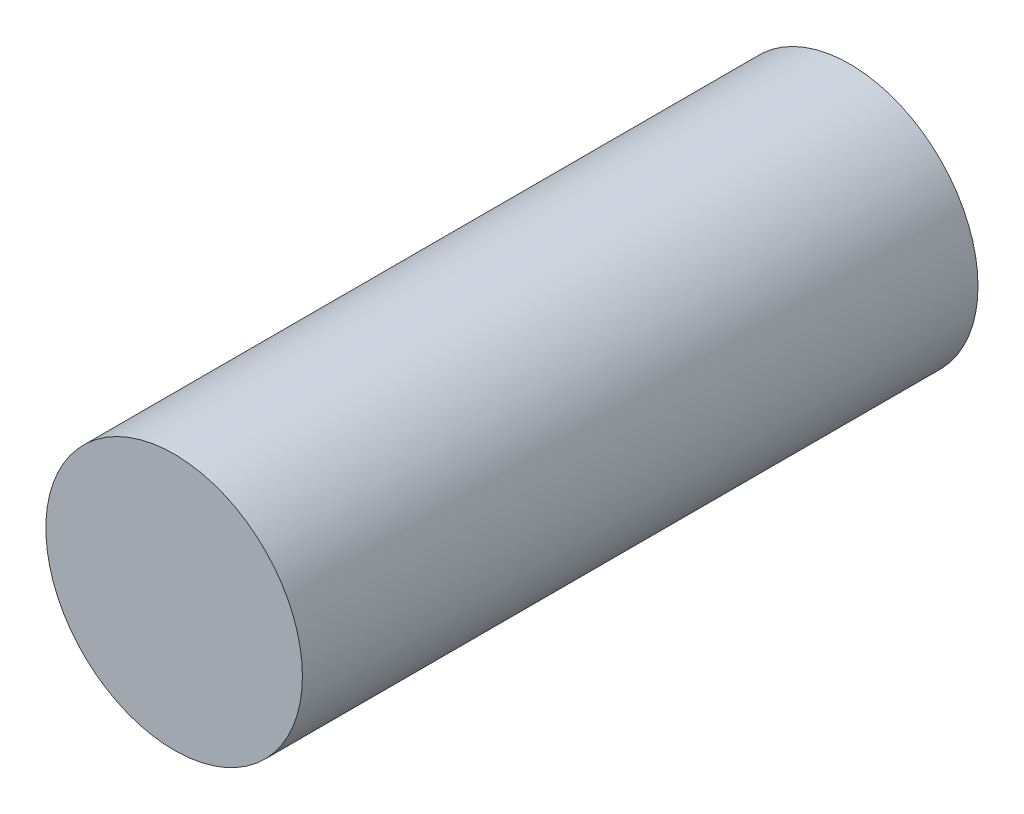
SolidWorks part; units mm, degrees
ref_plane "Front Plane" through (0, 0, 0) normal (0, 0, 1) x (1, 0, 0)
ref_plane "Top Plane" through (0, 0, 0) normal (0, 1, 0) x (1, 0, 0)
ref_plane "Right Plane" through (0, 0, 0) normal (1, 0, 0) x (0, 0, -1)
sketch "Sketch1" plane through (0, 0, 0) normal (0, 0, 1) x (1, 0, 0)
  circle A0 centre (0, 0) radius 1.5
  dimension "D1" = 3
extrude "Boss-Extrude1" add sketch "Sketch1" along normal blind 7.9 contours A0
sketch "Sketch2" plane through (0, 0, 7.9) normal (0, 0, 1) x (1, 0, 0)
  circle A0 centre (0, 0) radius 0.8
  dimension "D1" = 1.6
sketch "Sketch3" plane through (0, 0, 0) normal (0, 0, -1) x (-1, 0, 0)
  circle A0 centre (0, 0) radius 0.8
  dimension "D1" = 1.6
